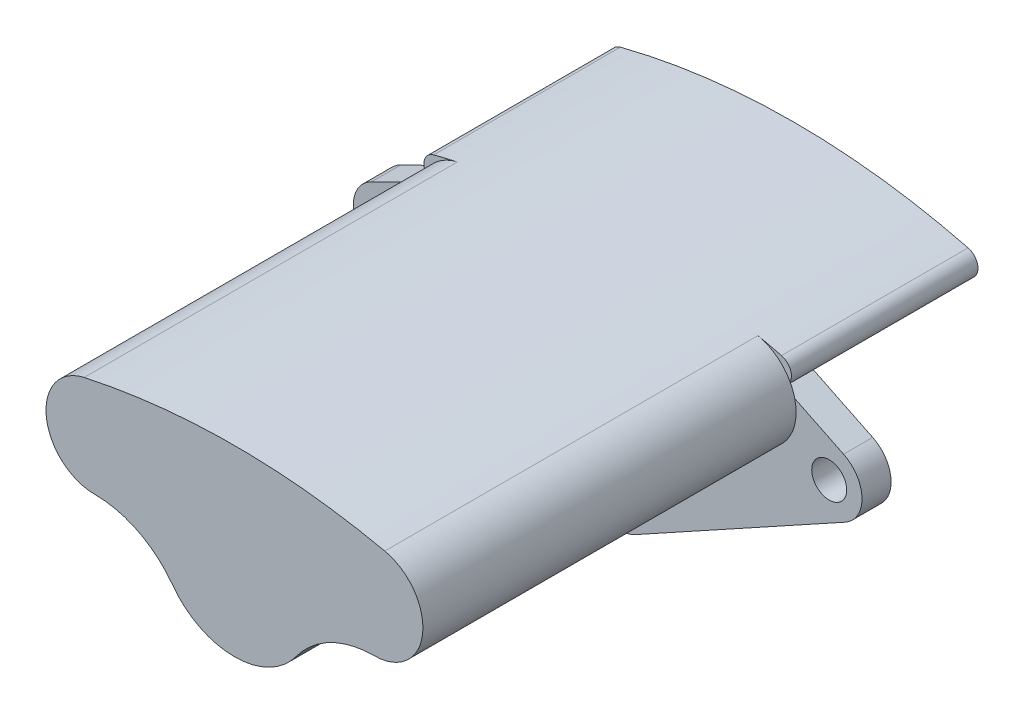
SolidWorks part; units mm, degrees
material "1023 Carbon Steel Sheet (SS)"
ref_plane "Front Plane" through (0, 0, 0) normal (0, 0, 1) x (1, 0, 0)
ref_plane "Top Plane" through (0, 0, 0) normal (0, 1, 0) x (1, 0, 0)
ref_plane "Right Plane" through (0, 0, 0) normal (1, 0, 0) x (0, 0, -1)
sketch "Sketch1" plane through (0, 0, 0) normal (0, 0, 1) x (1, 0, 0)
  line L0 (0, 46.0043) -> (0, -47.5161) construction
  circle A0 centre (0, 0) radius 15.113
  circle A2 centre (-60.325, 3.3006) radius 4.7625
  circle A3 centre (-38.1, 14.7306) radius 4.7625
  circle A4 centre (38.1, 14.7306) radius 4.7625
  circle A5 centre (60.325, 3.3006) radius 4.7625
  dimension "D1" = 30.226
  dimension "D2" = 9.525
  dimension "D9" = 9.525
  dimension "D5" = 60.325
  dimension "D7" = 38.1
  dimension "D10" = 11.43
sketch "Sketch3" plane through (0, 0, 0) normal (0, 0, 1) x (1, 0, 0)
  line L0 (-64.2346, 11.3235) -> (-41.7735, 22.269)
  line L1 (-30.4611, 18.1903) -> (-18.4402, -8.3516)
  line L2 (-64.6332, -4.5154) -> (-8.1092, -35.6719)
  line L3 (0, 56.8749) -> (0, -78.3641) construction
  line L4 (64.6332, -4.5154) -> (8.1092, -35.6719)
  line L5 (64.2346, 11.3235) -> (41.7735, 22.269)
  line L6 (30.4611, 18.1903) -> (18.4402, -8.3516)
  arc A0 (-64.2346, 11.3235) -> (-64.6332, -4.5154) centre (-60.325, 3.3006) ccw
  arc A1 (-41.7735, 22.269) -> (-30.4611, 18.1903) centre (-38.1, 14.7306) cw
  arc A2 (-18.4402, -8.3516) -> (18.4402, -8.3516) centre (0, 0) ccw
  arc A3 (-8.1092, -35.6719) -> (8.1092, -35.6719) centre (0, -20.9602) ccw
  arc A4 (64.2346, 11.3235) -> (64.6332, -4.5154) centre (60.325, 3.3006) cw
  arc A5 (41.7735, 22.269) -> (30.4611, 18.1903) centre (38.1, 14.7306) ccw
extrude "Boss-Extrude1" add sketch "Sketch3" along normal blind 7.9248
extrude "Cut-Extrude1" cut sketch "Sketch1" along normal through all
sketch "Sketch4" plane through (0, 0, 7.9248) normal (0, 0, 1) x (1, 0, 0)
  line L0 (0, -62.0323) -> (0, 85.1325) construction
  line L1 (0, 46.0043) -> (0, -47.5161) construction
  arc A0 (-40.9266, 27.6343) -> (0, 32.0644) centre (0, -159.1976) cw
  arc A1 (-40.9266, 27.6343) -> (-38.08, 1.521) centre (-38.1, 14.7306) ccw
  arc A2 (-38.08, 1.521) -> (-16.8662, -9.2104) centre (-38.0403, -24.7339) cw
  arc A3 (-16.8662, -9.2104) -> (0, -17.7585) centre (0, 3.1548) ccw
  arc A4 (16.8662, -9.2104) -> (0, -17.7585) centre (0, 3.1548) cw
  arc A5 (38.08, 1.521) -> (16.8662, -9.2104) centre (38.0403, -24.7339) ccw
  arc A6 (40.9266, 27.6343) -> (38.08, 1.521) centre (38.1, 14.7306) cw
  arc A7 (40.9266, 27.6343) -> (0, 32.0644) centre (0, -159.1976) ccw
  dimension "D1" = 191.262
extrude "Boss-Extrude2" add sketch "Sketch4" along normal blind 101.6
sketch "Sketch5" plane through (0, 0, 7.9248) normal (0, 0, -1) x (-1, 0, 0)
  line L0 (0, 70.5785) -> (0, -80.9467) construction
  arc A0 (-47.328, 26.1163) -> (47.328, 26.1163) centre (0, -159.1976) cw
  arc A1 (-47.328, 26.1163) -> (-45.5497, 19.1531) centre (-46.4388, 22.6347) ccw
  arc A2 (-45.5497, 19.1531) -> (45.5497, 19.1531) centre (0, -159.1976) cw
  arc A3 (47.328, 26.1163) -> (45.5497, 19.1531) centre (46.4388, 22.6347) cw
  arc A5 (40.9266, 27.6343) -> (-40.9266, 27.6343) centre (0, -159.1976) ccw construction
extrude "Boss-Extrude3" add sketch "Sketch5" along normal blind 50.8
sketch "Sketch6" plane through (0, 0, -42.8752) normal (0, 0, -1) x (-1, 0, 0)
  line L0 (-47.328, 26.1163) -> (-47.328, 4.4381)
  line L1 (-47.328, 4.4381) -> (47.328, 5.7194)
  line L2 (47.328, 5.7194) -> (47.328, 26.1163)
  arc A4 (-47.328, 26.1163) -> (-45.5497, 19.1531) centre (-46.4388, 22.6347) ccw
  arc A5 (45.5497, 19.1531) -> (-45.5497, 19.1531) centre (0, -159.1976) ccw
  arc A6 (45.5497, 19.1531) -> (47.328, 26.1163) centre (46.4388, 22.6347) ccw
  arc A7 (47.328, 26.1163) -> (-47.328, 26.1163) centre (0, -159.1976) ccw
  arc A11 (47.328, 26.1163) -> (-47.328, 26.1163) centre (0, -159.1976) ccw
  dimension "D1" = 0
extrude "Boss-Extrude4" [suppressed] add sketch "Sketch6" along normal blind 19.558
sketch "Sketch7" plane through (0, 0, 0) normal (0, 0, -1) x (-1, 0, 0)
  line L0 (-28.9884, 6.1897) -> (-28.9884, 23.4423)
  line L1 (-28.9884, 23.4423) -> (-47.625, 23.4423)
  line L2 (-47.625, 23.4423) -> (-47.625, 6.1897)
  line L3 (-47.625, 6.1897) -> (-21.0584, -15.6737)
  line L4 (0, 50.2441) -> (0, -57.5442) construction
  line L5 (47.625, 6.1897) -> (21.0584, -15.6737)
  line L6 (47.625, 23.4423) -> (47.625, 6.1897)
  line L7 (28.9884, 23.4423) -> (47.625, 23.4423)
  line L8 (28.9884, 6.1897) -> (28.9884, 23.4423)
  arc A0 (-21.0584, -15.6737) -> (21.0584, -15.6737) centre (0, -140.9157) cw
  arc A1 (-28.9884, 6.1897) -> (28.9884, 6.1897) centre (0, -140.9157) cw
  dimension "D3" = 127
  dimension "D1" = 95.25
  dimension "D2" = 39.116
sketch "Sketch8" plane through (0, 0, 0) normal (0, 0, -1) x (-1, 0, 0)
  line L1 (-79.9432, -50.9186) -> (80.1456, -50.9186)
  line L2 (-79.9432, -50.9186) -> (-79.9432, 25.584)
  line L3 (-79.9432, 25.584) -> (80.1456, 25.584)
  line L4 (80.1456, -50.9186) -> (80.1456, 25.584)
extrude "Cut-Extrude2" [suppressed] cut sketch "Sketch8" against normal blind 5.08
sketch "Sketch9" plane through (0, 0, 7.9248) normal (0, 0, -1) x (-1, 0, 0)
  circle A0 centre (0, -201.7811) radius 212.725
  dimension "D1" = 425.45
sketch "Sketch10" plane through (0, 0, 7.9248) normal (0, 0, -1) x (-1, 0, 0)
  line L4 (-2.5622, 64.7657) -> (-88.2965, 2.1753)
  line L5 (-88.2965, 2.1753) -> (-18.7248, -93.1218)
  line L6 (-18.7248, -93.1218) -> (139.0919, 22.0924)
  line L7 (139.0919, 22.0924) -> (-2.5622, 64.7657)
  line L8 (-2.5622, 64.7657) -> (-88.2965, 2.1753)
  line L9 (-88.2965, 2.1753) -> (-18.7248, -93.1218)
  line L10 (-18.7248, -93.1218) -> (139.0919, 22.0924)
  line L11 (139.0919, 22.0924) -> (-2.5622, 64.7657)
  dimension "D1" = 0
